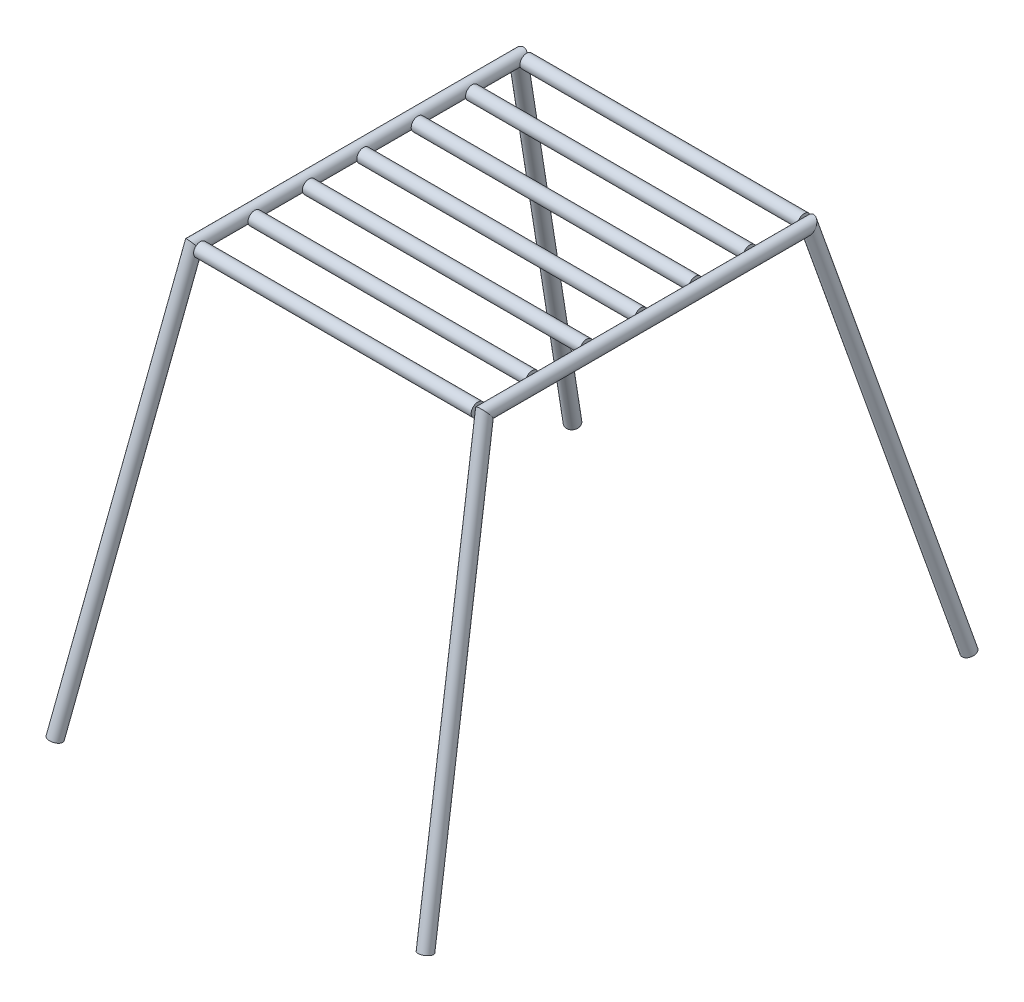
SolidWorks part; units mm, degrees
ref_plane "Front Plane" through (0, 0, 0) normal (0, 0, 1) x (1, 0, 0)
ref_plane "Top Plane" through (0, 0, 0) normal (0, 1, 0) x (1, 0, 0)
ref_plane "Right Plane" through (0, 0, 0) normal (1, 0, 0) x (0, 0, -1)
sketch3d "3DSketch2"
  line L0 (698, 673.3482, 1724.841) -> (548, 2173.3482, 1352.6153)
  line L1 (548, 2173.3482, 1352.6153) -> (548, 2173.3482, 129.1652)
  line L2 (548, 2173.3482, 129.1652) -> (747.1266, 679.8985, -274.5448)
  dimension "D1" = 2000
  dimension "D2" = 698
sweep "Sweep1" add path "3DSketch2" circular profile diameter 50 parameters "D3"=50
mirror "Mirror2" about plane through (0, 0, 0) normal (1, 0, 0) of bodies 101
sketch3d "3DSketch5"
  line L0 (523.1241, 2170.8607, 1352.6154) -> (-523.1241, 2170.8607, 1352.6154)
  spline S0 degree 3 poles (545.5124, 2198.2242, 1372.1932) (595.2643, 2203.1994, 1372.1932) (600.2395, 2153.4475, 1333.0374) (550.4876, 2148.4723, 1333.0374) (500.7357, 2143.4971, 1333.0374) (495.7605, 2193.249, 1372.1932) (545.5124, 2198.2242, 1372.1932) (595.2643, 2203.1994, 1372.1932) (600.2395, 2153.4475, 1333.0374) knots -0.5 0 0 0 0.5 0.5 0.5 1 1 1 1.5 1.5 1.5 weights 1 0.333333 0.333333 1 0.333333 0.333333 1 0.333333 0.333333 only from (545.5124, 2198.2242, 1372.1932) to (545.5124, 2198.2242, 1372.1932) construction
  spline S1 degree 3 poles (-545.5124, 2198.2242, 1372.1932) (-595.2643, 2203.1994, 1372.1932) (-600.2395, 2153.4475, 1333.0374) (-550.4876, 2148.4723, 1333.0374) (-500.7357, 2143.4971, 1333.0374) (-495.7605, 2193.249, 1372.1932) (-545.5124, 2198.2242, 1372.1932) (-595.2643, 2203.1994, 1372.1932) (-600.2395, 2153.4475, 1333.0374) knots -0.5 0 0 0 0.5 0.5 0.5 1 1 1 1.5 1.5 1.5 weights 1 0.333333 0.333333 1 0.333333 0.333333 1 0.333333 0.333333 only from (-545.5124, 2198.2242, 1372.1932) to (-545.5124, 2198.2242, 1372.1932) construction
sweep "Sweep4" add path "3DSketch5" circular profile diameter 50 parameters "D3"=50
pattern_linear "LPattern1" count 7 spacing 205 along (0, 0, -1) of "Sweep4"
